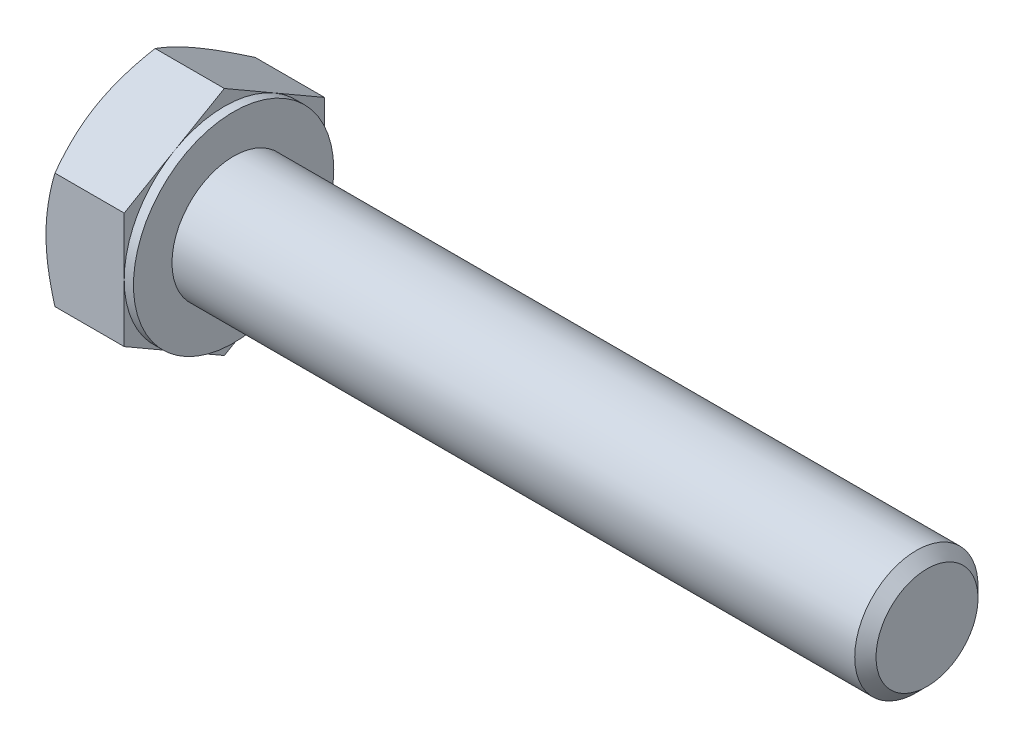
SolidWorks part; units mm, degrees
ref_plane "Plane1" through (0, 0, 0) normal (0, 0, 1) x (1, 0, 0)
ref_plane "Plane2" through (0, 0, 0) normal (0, 1, 0) x (1, 0, 0)
ref_plane "Plane3" through (0, 0, 0) normal (1, 0, 0) x (0, 0, -1)
sketch "Sketch1" plane through (0, 0, 0) normal (1, 0, 0) x (0, 0, -1)
  line L0 (6.5, 3.7528) -> (6.5, -3.7528)
  line L1 (-6.5, 3.7528) -> (-6.5, -3.7528)
  line L2 (6.5, -3.7528) -> (0, -7.5056)
  line L3 (0, -7.5056) -> (-6.5, -3.7528)
  line L4 (6.5, 3.7528) -> (0, 7.5056)
  line L5 (0, 7.5056) -> (-6.5, 3.7528)
  dimension "Width_flats" = 13
  dimension "D2" = 120
  dimension "D3" = 6.5
  dimension "D4" = 6.5
  dimension "D5" = 6.5
extrude "BaseHead" add sketch "Sketch1" along normal blind 5.675
sketch "BodySke" plane through (0, 0, 0) normal (0, 0, 1) x (1, 0, 0)
  line L0 (0, 3.7528) -> (0, -3.7528) construction
  line L1 (0, 0) -> (50.675, 0)
  line L2 (0, 0) -> (0, 4)
  line L3 (0, 4) -> (49.9845, 4)
  line L4 (50.675, 0) -> (50.675, 3.3095)
  line L5 (5.675, 7.5056) -> (5.675, 3.7528) construction
  line L6 (50.675, 3.3095) -> (49.9845, 4)
  line L7 (0, 0) -> (96.52, 0) construction
  line L8 (50.675, -3.3095) -> (49.9845, -4) construction
  line L9 (0, -4) -> (49.9845, -4) construction
  line L10 (6.925, 15.24) -> (6.925, -1.27) construction
  line L11 (28.675, 15.24) -> (28.675, -1.27) construction
  line L12 (5.675, 3.7528) -> (5.675, -3.7528) construction
  dimension "Length" = 45
  dimension "Body_ch_ang" = 45
  dimension "Diameter" = 8
  dimension "Minor_dia" = 6.619
  dimension "Advance" = 1.25
  dimension "Thread_nom" = 22
revolve "BaseBody" add sketch "BodySke"
cosmetic thread "ThreadCosmetic"
fillet "HeadFillet" [suppressed] radius 0.4
sketch "Sketch3" plane through (0, 0, 0) normal (0, 0, 1) x (1, 0, 0)
  line L0 (0, 6.5) -> (3.4673, 12.5056)
  line L1 (0, 7.5056) -> (0, 3.7528) construction
  line L2 (3.4673, 12.5056) -> (3.4673, 17.5056)
  line L3 (3.4673, 17.5056) -> (-10, 17.5056)
  line L4 (-10, 17.5056) -> (-10, 6.5)
  line L5 (-10, 6.5) -> (0, 6.5)
  line L6 (0, 0) -> (99.06, 0) construction
  line L7 (5.675, 7.5056) -> (0, 7.5056) construction
  dimension "D1" = 6.5
  dimension "D2" = 5
  dimension "D3" = 10
  dimension "D4" = 5
  dimension "Head_ch_ang" = 30
revolve "HeadChamfer" cut sketch "Sketch3" angle 360 about L6
sketch "Sketch4" plane through (0, 0, 0) normal (0, 0, 1) x (1, 0, 0)
  line L1 (5.675, 7.5056) -> (5.675, 3.7528) construction
  line L2 (5.675, 6.5) -> (5.075, 6.5)
  line L3 (5.675, 6.5) -> (5.675, 17.5056)
  line L4 (5.675, 17.5056) -> (5.075, 17.5056)
  line L5 (0, 0) -> (95.25, 0) construction
  line L6 (0, 0) -> (96.52, 0) construction
  line L7 (5.075, 6.5) -> (5.075, 17.5056)
  line L8 (5.675, 7.5056) -> (0.5806, 7.5056) construction
  dimension "D1" = 13
  dimension "D2" = 10
  dimension "Bearing_ht" = 0.6
revolve "BearingFace" cut sketch "Sketch4" angle 360 about L5
sketch "ThdSchSke" plane through (0, 0, 0) normal (0, 0, 1) x (1, 0, 0)
  line L0 (28.675, -3.3095) -> (28.1915, -4)
  line L1 (28.675, -3.3095) -> (29.1585, -4)
  line L2 (29.1585, -4) -> (29.1585, -5)
  line L3 (-3.175, 0) -> (5.1513, 0) construction
  line L5 (29.1585, -5) -> (28.1915, -5)
  line L6 (28.1915, -5) -> (28.1915, -4)
  dimension "Thread_minor" = 6.619
  dimension "Diameter" = 8
  dimension "Start" = 28.675
  dimension "SideAngle" = 55
  dimension "VeeAngle" = 70
  dimension "Overcut" = 10
revolve "ThreadSchematic" [suppressed] cut sketch "ThdSchSke" angle 360 about L3
pattern_linear "ThdSchPat" [suppressed]
equation "\"D3@Sketch1\" = \"Width_flats@Sketch1\" / 2"
equation "\"D4@Sketch1\" = \"D3@Sketch1\""
equation "\"D5@Sketch1\" = \"D4@Sketch1\""
equation "\"Thread_minor@ThreadCosmetic\" = \"Minor_dia@BodySke\""
equation "\"D1@Sketch3\" = \"Width_flats@Sketch1\" / 2"
equation "\"D1@Sketch4\" = \"Width_flats@Sketch1\""
equation "\"Thread_length@ThreadCosmetic\" = ((sgn( (\"Length@BodySke\" - \"Advance@BodySke\" ) - \"Thread_nom@BodySke\" )-1)*( (\"Length@BodySke\" - \"Advance@BodySke\" ) - \"Thread_nom@BodySke\" ))/-2+ \"Thread_nom@BodySke\""
equation "\"Thread_minor@ThdSchSke\" = \"Minor_dia@BodySke\""
equation "\"Diameter@ThdSchSke\" = \"Diameter@BodySke\""
equation "\"Overcut@ThdSchSke\" = \"Diameter@BodySke\" * 1.25"
equation "\"Start@ThdSchSke\" = \"Head_ht@BaseHead\" + \"Length@BodySke\" - \"Thread_length@ThreadCosmetic\"  '---Non-countersunk---"
equation "\"Num_threads@ThdSchPat\" = int( \"Thread_length@ThreadCosmetic\" / \"Advance@BodySke\" + 0.999 )  + 1"
equation "\"Advance@ThdSchPat\" = \"Thread_length@ThreadCosmetic\" /  (\"Num_threads@ThdSchPat\" - 1) 'relax it"
equation "\"Num_threads@ThdSchPat\" = \"Num_threads@ThdSchPat\" - sgn( \"Num_threads@ThdSchPat\" - 1) '---chamfered tips only---"
